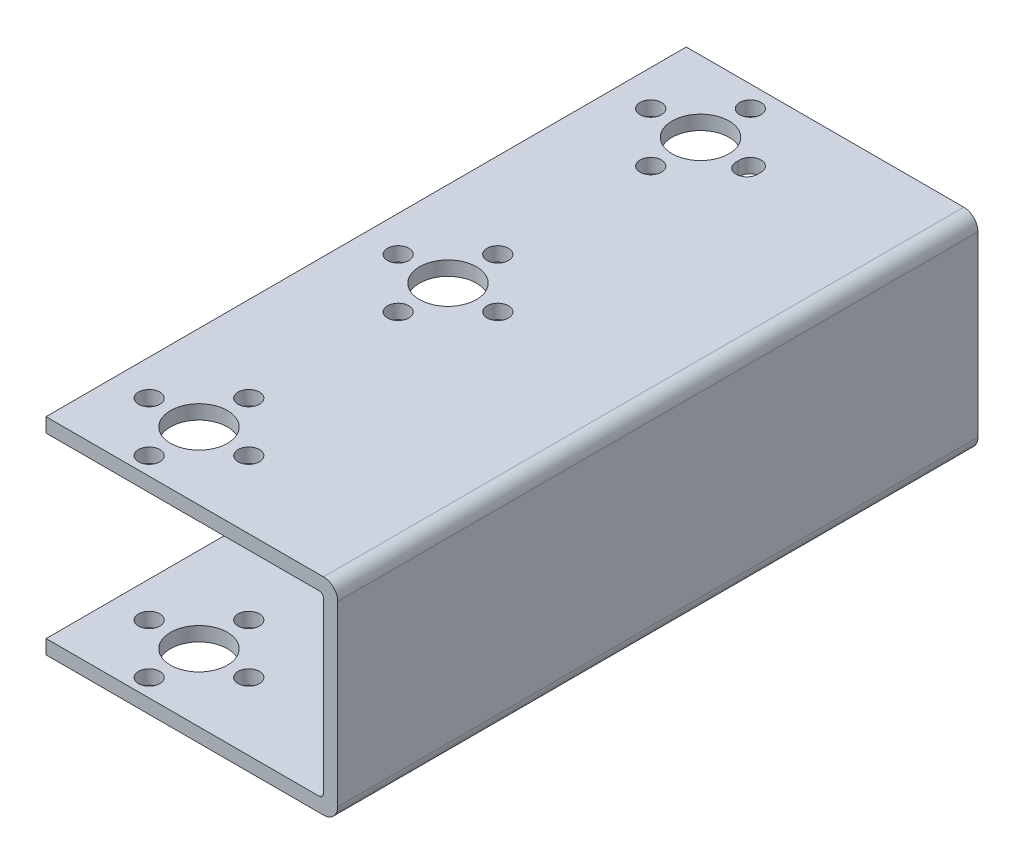
SolidWorks part; units mm, degrees
material "1060 Alloy"
ref_plane "Front Plane" through (0, 0, 0) normal (0, 0, 1) x (1, 0, 0)
ref_plane "Top Plane" through (0, 0, 0) normal (0, 1, 0) x (1, 0, 0)
ref_plane "Right Plane" through (0, 0, 0) normal (1, 0, 0) x (0, 0, -1)
sketch "Sketch3" plane through (0, 0, 0) normal (0, 0, 1) x (1, 0, 0)
  line L0 (-2, 0.0494) -> (-41, 0.0494)
  line L1 (-41, 0.0494) -> (-41, 2.0494)
  line L2 (-41, 2.0494) -> (-2.6183, 2.0494)
  line L4 (-0.0182, 27.0494) -> (-0.0182, 2.0494)
  line L5 (-2.0182, 29.0494) -> (-41.0182, 29.0494)
  line L6 (-41.0182, 29.0494) -> (-41.0182, 27.0494)
  line L7 (-41.0182, 27.0494) -> (-2.6183, 27.0494)
  line L8 (-2.6183, 2.6494) -> (-2.6183, 2.0494) construction
  line L9 (-2.0183, 26.4494) -> (-2.0183, 2.6494)
  line L10 (-2.6183, 2.6494) -> (-2.0183, 2.6494) construction
  arc A0 (-0.0182, 27.0494) -> (-2.0182, 29.0494) centre (-2.0182, 27.0494) ccw
  arc A1 (-0.0182, 2.0494) -> (-2, 0.0494) centre (-2.0183, 2.0494) cw
  arc A2 (-2.6183, 27.0494) -> (-2.0183, 26.4494) centre (-2.6183, 26.4494) cw
  arc A3 (-2.6183, 2.0494) -> (-2.0183, 2.6494) centre (-2.6183, 2.6494) ccw
  dimension "D1" = 0.6
  dimension "D2" = 0.6
  dimension "D3" = 2
  dimension "D4" = 0.6
extrude "Boss-Extrude1" add sketch "Sketch3" along normal blind 90
ref_plane "Plane1" through (0, 29.0494, 0) normal (0, 1, 0) x (1, 0, 0)
sketch "Sketch4" plane through (0, 29.0494, 0) normal (0, 1, 0) x (1, 0, 0)
  line L0 (-41.0182, 0) -> (-29.0182, 0)
  line L1 (-2.0182, 0) -> (-41.0182, 0) construction
  line L2 (-29.0182, 0) -> (-29.0182, -10)
  line L3 (-29.0182, -10) -> (-36.0182, -10) construction
  circle A0 centre (-29.0182, -10) radius 4
  circle A1 centre (-36.0182, -10) radius 1.5
  circle A2 centre (-29.0182, -3) radius 1.5
  circle A3 centre (-22.0182, -10) radius 1.5
  circle A4 centre (-29.0182, -17) radius 1.5
  point P18 (-29.0182, -10)
  dimension "D3" = 4
  dimension "D1" = 12
  dimension "D2" = 10
extrude "Cut-Extrude1" cut sketch "Sketch4" against normal blind 31
sketch "Sketch6" plane through (0, 29.0494, 0) normal (0, 1, 0) x (1, 0, 0)
  line L0 (-29.0182, -10) -> (-29.0182, -45.4989) construction
  line L1 (-29.0182, -45.4989) -> (-29.0182, -80.4989) construction
  line L2 (-36.0182, -10) -> (-36.0182, -45.4989) construction
  line L3 (-36.0182, -45.4989) -> (-36.0182, -80.4989) construction
  circle A0 centre (-29.0182, -45.4989) radius 4
  circle A1 centre (-29.0182, -80.4989) radius 4
  circle A2 centre (-36.0182, -45.4989) radius 1.5
  circle A3 centre (-36.0182, -80.4989) radius 1.5
  circle A4 centre (5.9818, -52.4989) radius 1.5
  circle A5 centre (-29.0182, -52.4989) radius 1.5
  circle A6 centre (-22.0182, -10.4989) radius 1.5
  circle A7 centre (-22.0182, -45.4989) radius 1.5
  circle A8 centre (-64.0182, -38.4989) radius 1.5
  circle A9 centre (-29.0182, -38.4989) radius 1.5
  circle A10 centre (-29.0182, -73.4989) radius 1.5
  circle A11 centre (-22.0182, -80.4989) radius 1.5
  circle A12 centre (-29.0182, -87.4989) radius 1.5
  point P27 (-29.0182, -45.4989)
  point P34 (-29.0182, -80.4989)
  dimension "D1" = 3
  dimension "D2" = 3
  dimension "D3" = 4
  dimension "D4" = 4
extrude "Cut-Extrude2" cut sketch "Sketch6" against normal blind 31
sketch "Sketch7" plane through (0, 29.0494, 0) normal (0, 1, 0) x (1, 0, 0)
  circle A0 centre (-22.0182, -45.4989) radius 1.5
